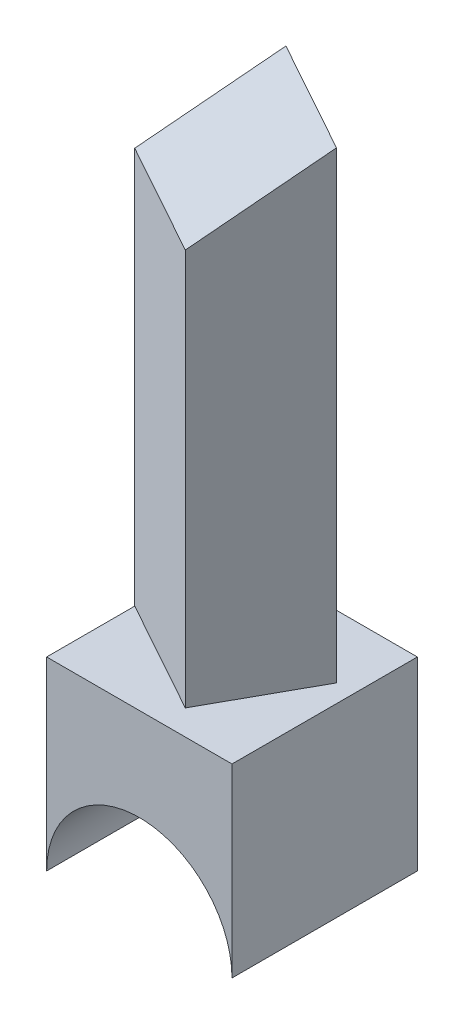
SolidWorks part; units mm, degrees
ref_plane "Front Plane" through (0, 0, 0) normal (0, 0, 1) x (1, 0, 0)
ref_plane "Top Plane" through (0, 0, 0) normal (0, 1, 0) x (1, 0, 0)
ref_plane "Right Plane" through (0, 0, 0) normal (1, 0, 0) x (0, 0, -1)
sketch "Sketch2" plane through (0, 0, 0) normal (0, 0, 1) x (1, 0, 0)
  line L1 (-50, 50) -> (50, 50)
  line L2 (-50, 50) -> (-50, -50)
  line L4 (50, 50) -> (50, -50)
  arc A0 (50, -50) -> (-50, -50) centre (0, -50) ccw
  point P0 (0, 0)
  dimension "D3" = 100
  dimension "D1" = 100
  dimension "D2" = 100
  dimension "D4" = 50
  dimension "D5" = 100
  dimension "D6" = 50
extrude "Boss-Extrude1" add sketch "Sketch2" along normal blind 100
sketch "Sketch4" plane through (0, 50, 0) normal (0, 1, 0) x (1, 0, 0)
  line L0 (-20.9114, 0) -> (40.312, -33.9367)
  line L1 (-50, -100) -> (-50, 0) construction
  line L2 (40.312, -33.9367) -> (11.2234, -86.4139)
  line L3 (11.2234, -86.4139) -> (-50, -52.4772)
  line L5 (50, 0) -> (-50, 0) construction
  line L6 (-20.9114, 0) -> (-50, -52.4772)
  point P0 (40.312, -33.9367)
  dimension "D1" = 29
  dimension "D3" = 60
  dimension "58" = 70
extrude "Boss-Extrude2" add sketch "Sketch4" along normal blind 250
sketch "Sketch5" plane through (45.227, 0, 25.0697) normal (0.8746, 0, 0.4848) x (0.4848, 0, -0.8746)
  line L0 (-10.1381, 300) -> (-70.1381, 263.9484)
  line L1 (-70.1381, 300) -> (-70.1381, 50) construction
  line L2 (-70.1381, 263.9484) -> (-70.1381, 300)
  line L3 (-70.1381, 300) -> (-10.1381, 300) construction
  line L4 (-70.1381, 300) -> (-10.1381, 300)
  dimension "D1" = 31
extrude "Cut-Extrude1" cut sketch "Sketch5" against normal blind 70
